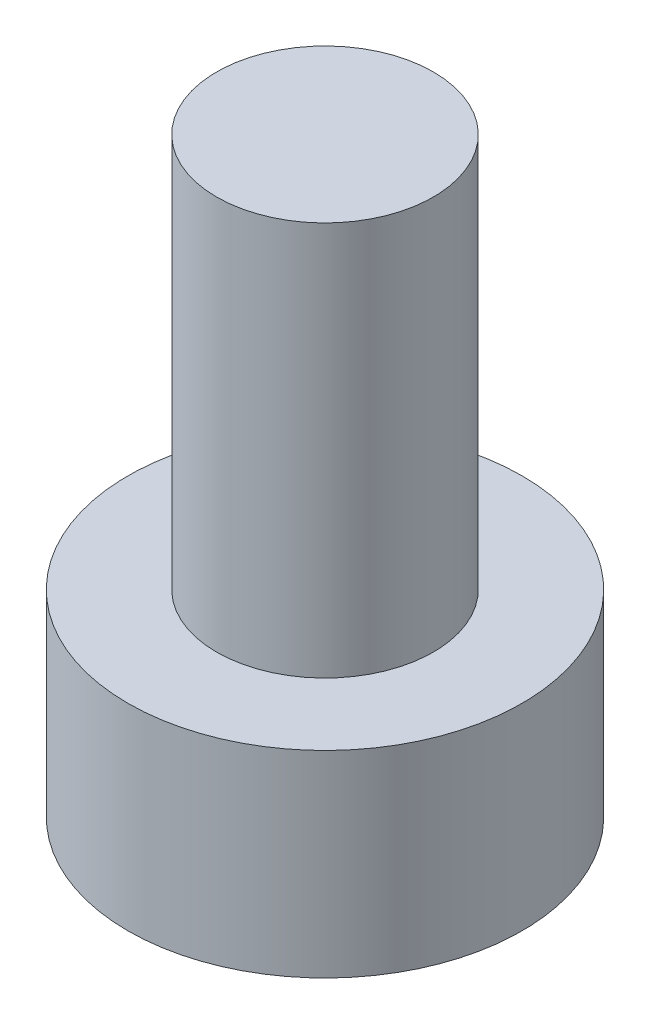
SolidWorks part; units mm, degrees
ref_plane "Front Plane" through (0, 0, 0) normal (0, 0, 1) x (1, 0, 0)
ref_plane "Top Plane" through (0, 0, 0) normal (0, 1, 0) x (1, 0, 0)
ref_plane "Right Plane" through (0, 0, 0) normal (1, 0, 0) x (0, 0, -1)
sketch "Sketch1" plane through (0, 0, 0) normal (0, 1, 0) x (1, 0, 0)
  circle A0 centre (0, 0) radius 2
  dimension "D1" = 4
extrude "Boss-Extrude1" add sketch "Sketch1" along normal blind 2 contours A0
sketch "Sketch2" plane through (0, 0, 0) normal (0, -1, 0) x (1, 0, 0)
  line L1 (1.3071, -0.1166) -> (0.7545, 1.0737)
  line L2 (0.7545, 1.0737) -> (-0.5526, 1.1903)
  line L3 (-0.5526, 1.1903) -> (-1.3071, 0.1166)
  line L4 (-1.3071, 0.1166) -> (-0.7545, -1.0737)
  line L5 (-0.7545, -1.0737) -> (0.5526, -1.1903)
  line L6 (0.5526, -1.1903) -> (1.3071, -0.1166)
  circle A0 centre (0, 0) radius 1.1365 construction
extrude "Cut-Extrude1" cut sketch "Sketch2" against normal blind 1
sketch "Sketch3" plane through (0, 2, 0) normal (0, 1, 0) x (1, 0, 0)
  circle A0 centre (0, 0) radius 1.1
extrude "Boss-Extrude2" add sketch "Sketch3" along normal blind 4 contours A0
